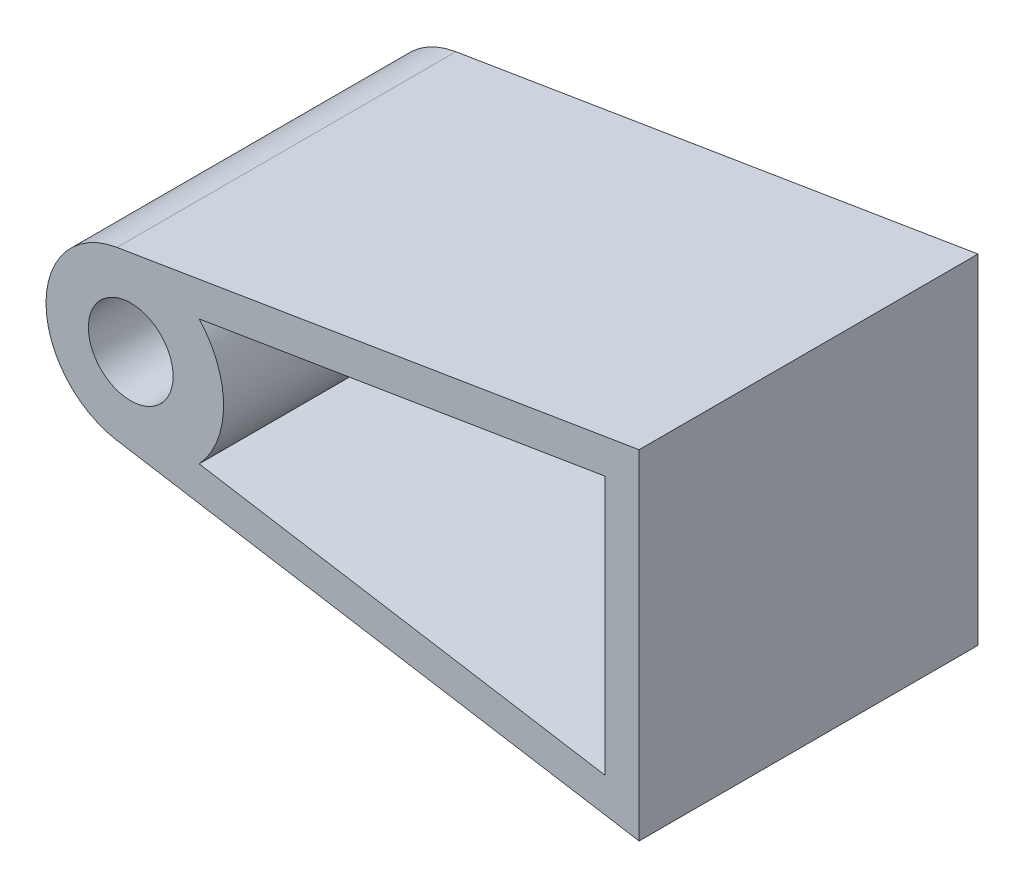
SolidWorks part; units mm, degrees
ref_plane "前视基准面" through (0, 0, 0) normal (0, 0, 1) x (1, 0, 0)
ref_plane "上视基准面" through (0, 0, 0) normal (0, 1, 0) x (1, 0, 0)
ref_plane "右视基准面" through (0, 0, 0) normal (1, 0, 0) x (0, 0, -1)
other "Configuration Table"
sketch "草图1" plane through (0, 0, 0) normal (0, 0, 1) x (1, 0, 0)
  line L0 (0, 10) -> (0, -10)
  line L1 (0, -10) -> (-30.8112, -4.9337)
  line L2 (0, 0) -> (16.7393, 0) construction
  line L3 (0, 10) -> (-30.8112, 4.9337)
  arc A0 (-30.8112, 4.9337) -> (-30.8112, -4.9337) centre (-30, 0) ccw
  circle A1 centre (-30, 0) radius 2.5
  dimension "D1" = 10
  dimension "D4" = 5
  dimension "D2" = 10
  dimension "D3" = 30
extrude "凸台-拉伸1" add sketch "草图1" along normal mid plane 20
sketch "草图2" plane through (0, 0, 10) normal (0, 0, 1) x (1, 0, 0)
  line L18 (-30.4867, -2.9602) -> (-2, -7.6443)
  line L19 (-2, -7.6443) -> (-2, 7.6443)
  line L20 (-2, 7.6443) -> (-30.4867, 2.9602)
  line L21 (-25.9608, -3.7044) -> (-2, -7.6443)
  line L22 (-2, -7.6443) -> (-2, 7.6443)
  line L23 (-2, 7.6443) -> (-25.9608, 3.7044)
  arc A10 (-25.9608, -3.7044) -> (-25.9608, 3.7044) centre (-30, 0) ccw
  arc A11 (-30.4867, 2.9602) -> (-30.4867, -2.9602) centre (-30, 0) ccw
  dimension "D1" = 2
extrude "切除-拉伸1" cut sketch "草图2" against normal through all
